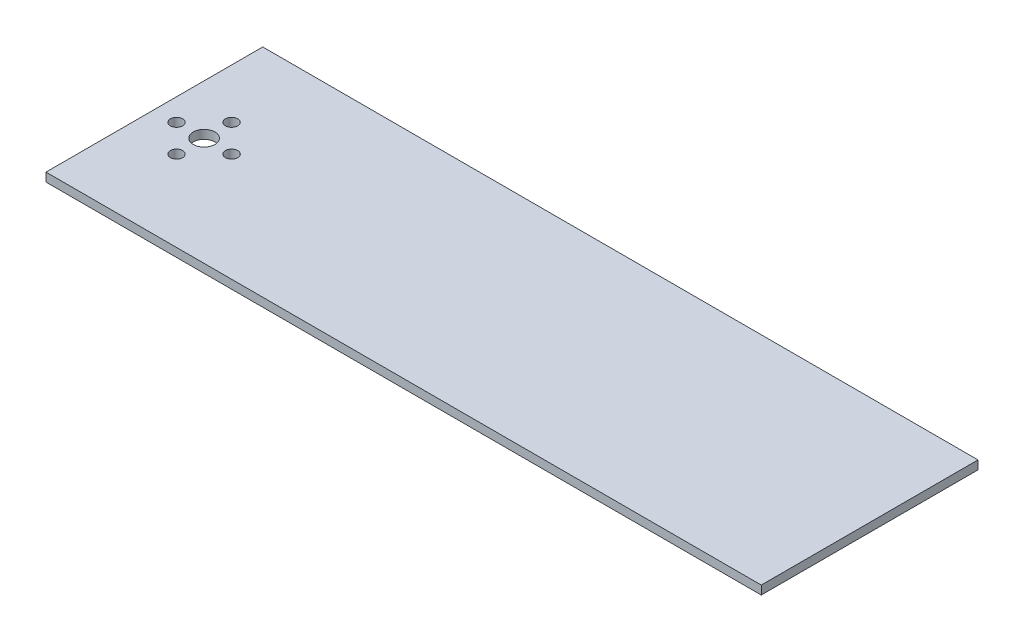
SolidWorks part; units mm, degrees
ref_plane "Front Plane" through (0, 0, 0) normal (0, 0, 1) x (1, 0, 0)
ref_plane "Top Plane" through (0, 0, 0) normal (0, 1, 0) x (1, 0, 0)
ref_plane "Right Plane" through (0, 0, 0) normal (1, 0, 0) x (0, 0, -1)
sketch "Sketch1" plane through (0, 0, 0) normal (0, 1, 0) x (1, 0, 0)
  line L1 (-82.5, -25) -> (82.5, -25)
  line L2 (-82.5, -25) -> (-82.5, 25)
  line L3 (-82.5, 25) -> (82.5, 25)
  line L4 (82.5, -25) -> (82.5, 25)
  line L5 (-82.5, -25) -> (82.5, 25) construction
  line L6 (-82.5, 25) -> (82.5, -25) construction
  point P0 (0, 0)
  dimension "D1" = 165
  dimension "D2" = 50
extrude "Boss-Extrude1" add sketch "Sketch1" along normal blind 2
sketch "Sketch2" plane through (0, 2, 0) normal (0, 1, 0) x (1, 0, 0)
  circle A0 centre (-71.0374, 0) radius 2.5
  circle A1 centre (-71.0374, 6.35) radius 1.42
  circle A2 centre (-77.3874, 0) radius 1.42
  circle A3 centre (-71.0374, -6.35) radius 1.42
  circle A4 centre (-64.6874, 0) radius 1.42
  point P13 (-71.0374, 0)
  dimension "D1" = 5
  dimension "D3" = 2.84
  dimension "D2" = 6.35
  dimension "D4" = 4
extrude "Cut-Extrude1" cut sketch "Sketch2" against normal blind 2
